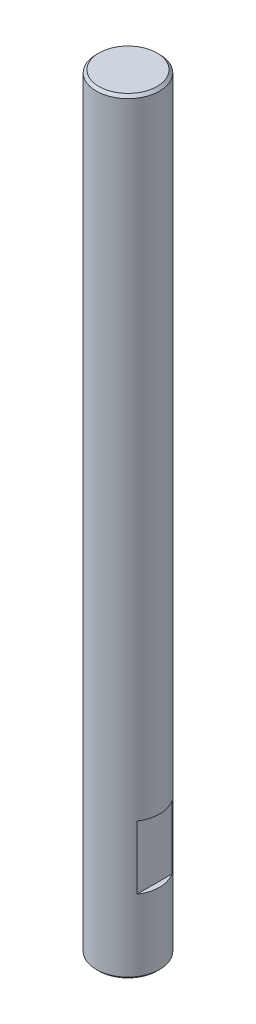
SolidWorks part; units mm, degrees
ref_plane "Front Plane" through (0, 0, 0) normal (0, 0, 1) x (1, 0, 0)
ref_plane "Top Plane" through (0, 0, 0) normal (0, 1, 0) x (1, 0, 0)
ref_plane "Right Plane" through (0, 0, 0) normal (1, 0, 0) x (0, 0, -1)
sketch "Sketch1" plane through (0, 0, 0) normal (0, 1, 0) x (1, 0, 0)
  circle A0 centre (0, 0) radius 6
  dimension "D1" = 12
extrude "Boss-Extrude1" add sketch "Sketch1" along normal blind 145
chamfer "Chamfer1" distance 0.5 angle 45 2 edges at (0, 0, 6) (0, 145, 6)
sketch "Sketch2" plane through (0, 0, 0) normal (0, 0, 1) x (1, 0, 0)
  line L0 (6, 0.5) -> (6, 144.5) construction
  line L1 (6, 26) -> (5, 26)
  line L2 (6, 26) -> (6, 14)
  line L3 (6, 14) -> (5, 14)
  line L4 (5, 26) -> (5, 14)
  line L5 (0, 0) -> (0, 145) construction
  line L6 (5.5, 145) -> (-5.5, 145) construction
  line L8 (-5.5, 0) -> (5.5, 0) construction
  point P11 (5.5, 14)
  dimension "D1" = 5
  dimension "D2" = 12
  dimension "D3" = 14
extrude "Cut-Extrude1" cut sketch "Sketch2" against normal through all and the other way through all
